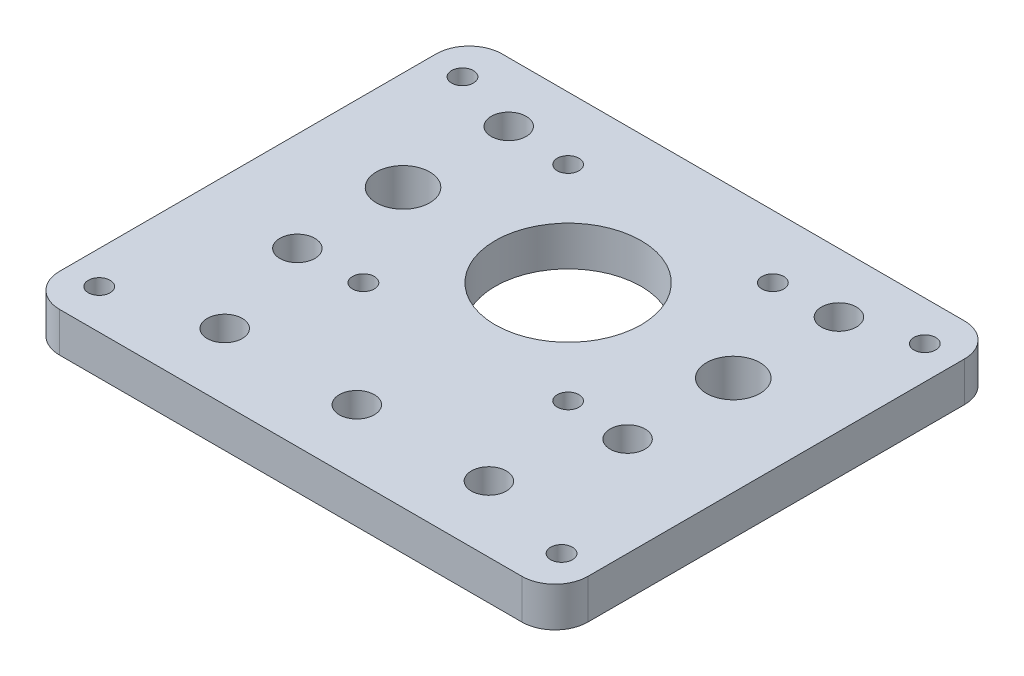
SolidWorks part; units mm, degrees
ref_plane "前视基准面" through (0, 0, 0) normal (0, 0, 1) x (1, 0, 0)
ref_plane "上视基准面" through (0, 0, 0) normal (0, 1, 0) x (1, 0, 0)
ref_plane "右视基准面" through (0, 0, 0) normal (1, 0, 0) x (0, 0, -1)
other "Configuration Table"
sketch "草图1" plane through (0, 0, 0) normal (0, 1, 0) x (1, 0, 0)
  line L0 (0, 34.5646) -> (0, -40.5221) construction
  line L1 (-49.2335, 0) -> (52.0436, 0) construction
  line L2 (-49.2335, -15.5) -> (52.0436, -15.5) construction
  line L3 (-15.5, 34.5646) -> (-15.5, -50.199) construction
  line L4 (-49.2335, 15.5) -> (52.0436, 15.5) construction
  line L5 (15.5, 34.5646) -> (15.5, -50.199) construction
  line L6 (-25, 34.5646) -> (-25, -50.199) construction
  line L7 (21.2, 34.5646) -> (21.2, -50.199) construction
  line L8 (-49.2335, -21.2) -> (52.0436, -21.2) construction
  line L9 (-49.2335, 21.2) -> (52.0436, 21.2) construction
  line L10 (-49.2335, -16) -> (52.0436, -16) construction
  line L11 (-49.2335, 16) -> (52.0436, 16) construction
  line L12 (-49.2335, -21.5) -> (52.0436, -21.5) construction
  line L13 (-49.2335, 21.5) -> (52.0436, 21.5) construction
  line L14 (-49.2335, -32) -> (52.0436, -32) construction
  line L15 (-49.2335, 30) -> (52.0436, 30) construction
  line L16 (-20, 34.5646) -> (-20, -50.199) construction
  line L17 (20, 34.5646) -> (20, -50.199) construction
  line L18 (-21.2, 34.5646) -> (-21.2, -50.199) construction
  line L19 (-40, 20) -> (-40, -37)
  line L20 (40, 20) -> (40, -37)
  line L21 (-35, -42) -> (35, -42)
  line L22 (-49.2335, -22) -> (52.0436, -22) construction
  line L23 (-15.5, 34.5646) -> (-15.5, -40.5221) construction
  line L24 (-20, 34.5646) -> (-20, -40.5221) construction
  line L25 (-21.2, 34.5646) -> (-21.2, -40.5221) construction
  line L26 (-25, 34.5646) -> (-25, -40.5221) construction
  line L27 (-40, 34.5646) -> (-40, -40.5221) construction
  line L28 (15.5, 34.5646) -> (15.5, -40.5221) construction
  line L29 (20, 34.5646) -> (20, -40.5221) construction
  line L30 (21.2, 34.5646) -> (21.2, -40.5221) construction
  line L31 (40, 34.5646) -> (40, -40.5221) construction
  line L32 (-35, 25) -> (35, 25)
  line L33 (-49.2335, 25) -> (52.0436, 25) construction
  line L34 (-49.2335, -42) -> (52.0436, -42) construction
  line L35 (-35, 34.5646) -> (-35, -40.5221) construction
  circle A0 centre (0, 0) radius 11.05
  circle A1 centre (-15.5, 15.5) radius 1.65
  circle A2 centre (15.5, 15.5) radius 1.65
  circle A3 centre (15.5, -15.5) radius 1.65
  circle A4 centre (-15.5, -15.5) radius 1.65
  circle A5 centre (-25, 0) radius 4.05
  circle A6 centre (-25, 16) radius 2.65
  circle A7 centre (-25, -16) radius 2.65
  circle A8 centre (25, -16) radius 2.65
  circle A9 centre (25, 16) radius 2.65
  circle A10 centre (25, 0) radius 4.05
  circle A11 centre (-20, -32) radius 2.65
  circle A12 centre (0, -32) radius 2.65
  circle A13 centre (20, -32) radius 2.65
  arc A14 (-35, 25) -> (-40, 20) centre (-35, 20) ccw
  arc A15 (-40, -37) -> (-35, -42) centre (-35, -37) ccw
  arc A16 (-35, -42) -> (-40, -37) centre (-35, -37) cw
  arc A17 (35, -42) -> (40, -37) centre (35, -37) ccw
  arc A18 (40, 20) -> (35, 25) centre (35, 20) ccw
  circle A19 centre (-35, 19) radius 1.65
  circle A20 centre (-35, -36) radius 1.65
  circle A21 centre (35, -36) radius 1.65
  circle A22 centre (35, 19) radius 1.65
  point P26 (0, 0)
  dimension "D1" = 22.1
  dimension "D4" = 3.3
  dimension "D10" = 8.1
  dimension "D13" = 5.3
  dimension "D14" = 21.5
  dimension "D20" = 5.3
  dimension "D28" = 5
  dimension "D29" = 5
  dimension "D34" = 3.3
  dimension "D35" = 3.3
  dimension "D31" = 70
  dimension "D32" = 6
  dimension "D33" = 6
  dimension "D36" = 70
  dimension "D2" = 15.5
  dimension "D3" = 15.5
  dimension "D6" = 25
  dimension "D7" = 21.2
  dimension "D8" = 21.2
  dimension "D9" = 21.2
  dimension "D11" = 16
  dimension "D12" = 16
  dimension "D15" = 21.5
  dimension "D16" = 32
  dimension "D17" = 30
  dimension "D18" = 20
  dimension "D19" = 20
  dimension "D22" = 21.2
  dimension "D23" = 40
  dimension "D24" = 40
  dimension "D25" = 10
  dimension "D26" = 10
  dimension "D27" = 25
  dimension "D30" = 35
  dimension "D21" = 3
  dimension "D5" = 4
extrude "凸台-拉伸1" add sketch "草图1" along normal blind 6 contours L20 A18 L32 A14 L19 A15 L21 A17 A10 A7 A6 A5 A4 A3 A2 A1 A0 A8 A9 A11 A12 A13
sketch "草图4" plane through (0, 0, 0) normal (0, 1, 0) x (1, 0, 0)
  line L0 (21.1472, -39.5864) -> (31.2375, -39.5864) construction
  text T0 "<b>wxy</b>"
extrude "凸台-拉伸7" add sketch "草图4" against normal blind 1 from surface at 0 starting at face at (35, 0, 37.65)
